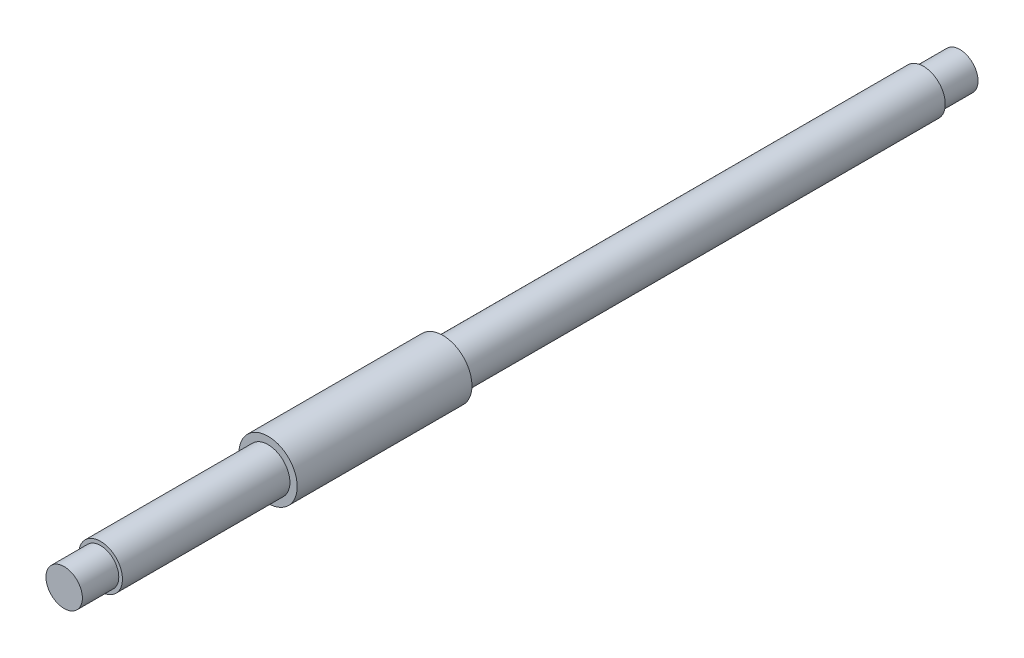
SolidWorks part; units mm, degrees
ref_plane "前视基准面" through (0, 0, 0) normal (0, 0, 1) x (1, 0, 0)
ref_plane "上视基准面" through (0, 0, 0) normal (0, 1, 0) x (1, 0, 0)
ref_plane "右视基准面" through (0, 0, 0) normal (1, 0, 0) x (0, 0, -1)
other "Configuration Table"
sketch "草图1" plane through (0, 0, 0) normal (0, 0, 1) x (1, 0, 0)
  circle A0 centre (0, 0) radius 4
  dimension "D1" = 8
extrude "凸台-拉伸1" add sketch "草图1" along normal blind 24
sketch "草图2" plane through (0, 0, 24) normal (0, 0, 1) x (1, 0, 0)
  circle A0 centre (0, 0) radius 3
  dimension "D1" = 6
extrude "凸台-拉伸2" add sketch "草图2" along normal blind 23
sketch "草图3" plane through (0, 0, 0) normal (0, 0, -1) x (-1, 0, 0)
  circle A0 centre (0, 0) radius 3
  dimension "D1" = 6
extrude "凸台-拉伸3" add sketch "草图3" along normal blind 66 contours A0
sketch "草图4" plane through (0, 0, -66) normal (0, 0, -1) x (-1, 0, 0)
  circle A0 centre (0, 0) radius 2.5
  dimension "D1" = 5
extrude "凸台-拉伸4" add sketch "草图4" along normal blind 5 contours A0
sketch "草图6" plane through (0, 0, 47) normal (0, 0, 1) x (1, 0, 0)
  circle A0 centre (0, 0) radius 2.5
  dimension "D1" = 5
extrude "凸台-拉伸5" add sketch "草图6" along normal blind 5
